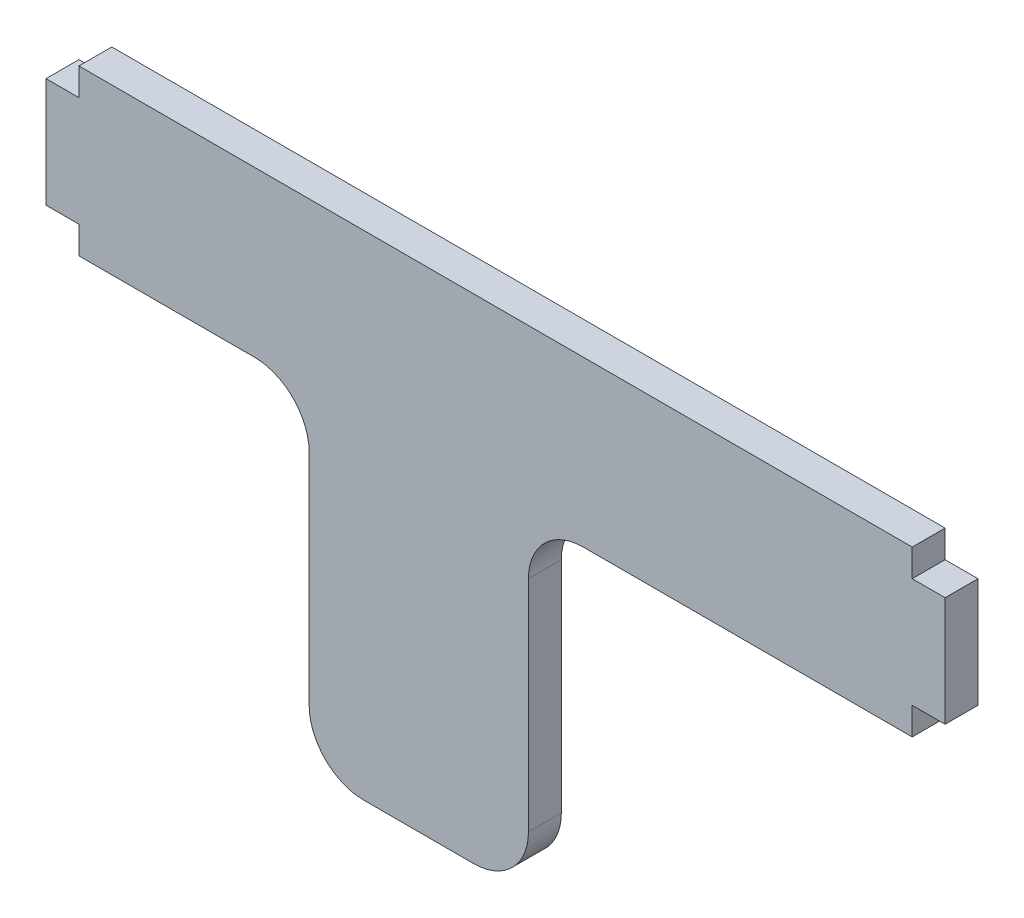
SolidWorks part; units mm, degrees
ref_plane "Plano frontal" through (0, 0, 0) normal (0, 0, 1) x (1, 0, 0)
ref_plane "Plano superior" through (0, 0, 0) normal (0, 1, 0) x (1, 0, 0)
ref_plane "Plano direito" through (0, 0, 0) normal (1, 0, 0) x (0, 0, -1)
sketch "Esboço1" plane through (0, 0, 0) normal (0, 0, 1) x (1, 0, 0)
  line L0 (0, 0) -> (0, 7.5) construction
  line L1 (38, -7.5) -> (-38, -7.5)
  line L2 (38, -7.5) -> (38, 7.5)
  line L3 (38, 7.5) -> (-38, 7.5)
  line L4 (-38, -7.5) -> (-38, 7.5)
  line L5 (38, -7.5) -> (-38, 7.5) construction
  line L6 (38, 7.5) -> (-38, -7.5) construction
  line L7 (3, -37.5) -> (-17, -37.5)
  line L8 (3, -37.5) -> (3, -7.5)
  line L9 (3, -7.5) -> (-17, -7.5)
  line L10 (-17, -37.5) -> (-17, -7.5)
  line L11 (3, -37.5) -> (-17, -7.5) construction
  line L12 (3, -7.5) -> (-17, -37.5) construction
  line L13 (-41, -5) -> (-38, -5)
  line L14 (-41, -5) -> (-41, 5)
  line L15 (-41, 5) -> (-38, 5)
  line L16 (-38, -5) -> (-38, 5)
  line L17 (-41, -5) -> (-38, 5) construction
  line L18 (-41, 5) -> (-38, -5) construction
  line L19 (41, 5) -> (38, 5)
  line L20 (38, -5) -> (38, 5)
  line L21 (41, -5) -> (38, -5)
  line L22 (41, -5) -> (41, 5)
  point P0 (0, 0)
  point P6 (-7, -22.5)
  point P12 (-39.5, 0)
  dimension "D1" = 76
  dimension "D2" = 30
  dimension "D3" = 15
  dimension "D4" = 20
  dimension "D5" = 3
  dimension "D6" = 10
  dimension "D7" = 48
extrude "Ressalto-extrusão1" add sketch "Esboço1" along normal blind 3 contours L4 L1 L2 L3 | L10 L7 L8 L1 | L21 L22 L19 L2 | L15 L14 L13 L4
fillet "Filete1" radius 5 4 edges at (3, -37.5, 1.5) (-17, -37.5, 1.5) (-17, -7.5, 1.5) (3, -7.5, 1.5)
